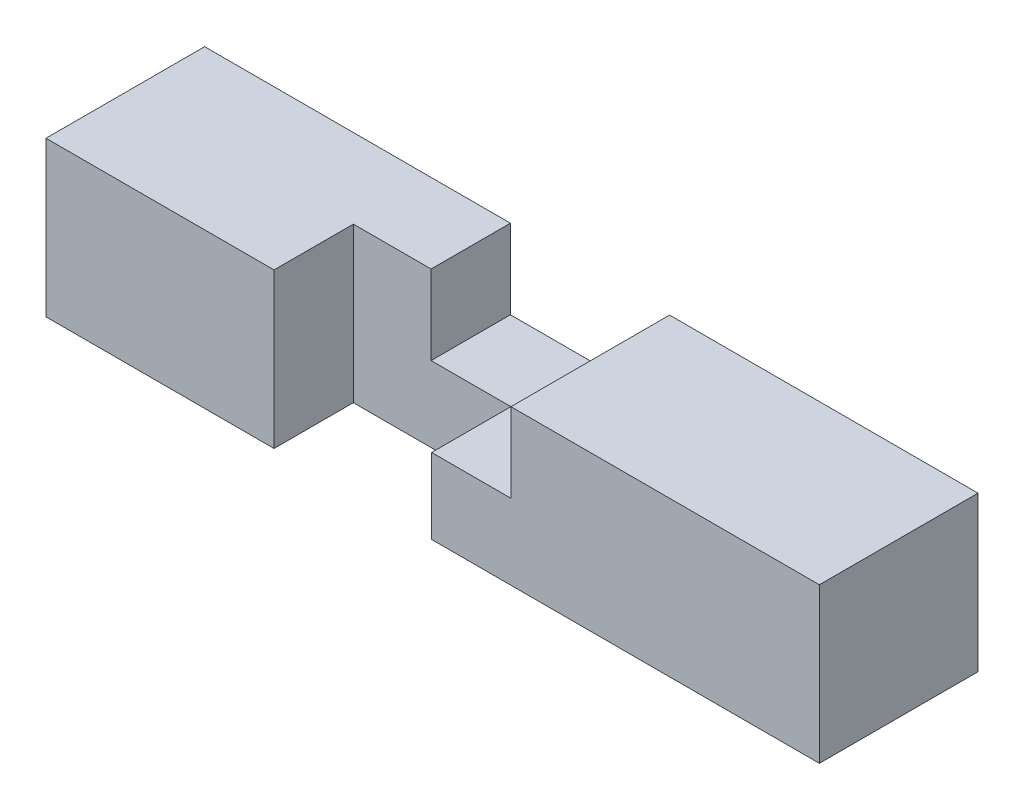
SolidWorks part; units mm, degrees
ref_plane "前基準面" through (0, 0, 0) normal (0, 0, 1) x (1, 0, 0)
ref_plane "上基準面" through (0, 0, 0) normal (0, 1, 0) x (1, 0, 0)
ref_plane "右基準面" through (0, 0, 0) normal (1, 0, 0) x (0, 0, -1)
sketch "草圖1" plane through (0, 0, 0) normal (0, 0, 1) x (1, 0, 0)
  line L1 (-48.75, 9.75) -> (48.75, 9.75)
  line L2 (-48.75, 9.75) -> (-48.75, -9.75)
  line L3 (-48.75, -9.75) -> (48.75, -9.75)
  line L4 (48.75, 9.75) -> (48.75, -9.75)
  line L5 (0, -9.75) -> (0, 9.75) construction
  line L6 (-48.75, 0) -> (48.75, 0) construction
  point P0 (0, 0)
extrude "填料-伸長1" add sketch "草圖1" along normal blind 20
sketch "草圖2" plane through (0, 9.75, 0) normal (0, 1, 0) x (1, 0, 0)
  line L0 (0, 0) -> (0, -20) construction
  line L3 (-50, -10) -> (50, -10) construction
  line L11 (0, -10) -> (0, -30) construction
  line L12 (20, -20) -> (-20, -20) construction
  line L13 (-20, -10) -> (-20, -20)
  line L15 (-20, -10) -> (9.8653, -10)
  line L17 (-20, -20) -> (9.8653, -20)
  line L18 (9.8653, -10) -> (9.8653, -20)
extrude "除料-伸長4" cut sketch "草圖2" against normal blind 29
sketch "草圖3" plane through (0, 9.75, 0) normal (0, 1, 0) x (1, 0, 0)
  line L0 (48.75, -20) -> (9.8653, -20) construction
  line L1 (9.8653, -10) -> (19.8653, -10)
  line L2 (9.8653, -10) -> (9.8653, -20)
  line L3 (9.8653, -20) -> (19.8653, -20)
  line L4 (19.8653, -10) -> (19.8653, -20)
extrude "除料-伸長5" cut sketch "草圖3" against normal blind 10
sketch "草圖4" plane through (0, 9.75, 0) normal (0, 1, 0) x (1, 0, 0)
  line L0 (0, 0) -> (-0.0674, -10) construction
  line L1 (48.75, 0) -> (-48.75, 0) construction
  line L2 (19.8653, -10) -> (-20, -10) construction
  line L4 (0, 0) -> (19.8653, 0)
  line L5 (0, 0) -> (0, -10)
  line L6 (0, -10) -> (19.8653, -10)
  line L7 (19.8653, 0) -> (19.8653, -10)
extrude "除料-伸長6" cut sketch "草圖4" against normal blind 10
sketch "草圖5" plane through (0, 9.75, 0) normal (0, 1, 0) x (1, 0, 0)
  line L0 (0, -10) -> (-20, -10) construction
  line L1 (0, 0) -> (-10, 0)
  line L2 (0, 0) -> (0, -10)
  line L3 (0, -10) -> (-10, -10)
  line L4 (-10, 0) -> (-10, -10)
extrude "除料-伸長7" cut sketch "草圖5" against normal blind 10
shell "薄殼1" thickness 2
sketch "草圖7" plane through (0, 9.75, 0) normal (0, 1, 0) x (1, 0, 0)
  line L1 (-20, -10) -> (-10, -10)
  line L2 (-20, -10) -> (-20, 0)
  line L3 (-20, 0) -> (-10, 0)
  line L4 (-10, -10) -> (-10, 0)
extrude "除料-伸長8" cut sketch "草圖7" against normal blind 10
sketch "草圖8" plane through (0, 9.75, 0) normal (0, 1, 0) x (1, 0, 0)
  line L0 (-20, 0) -> (-20, -20) construction
  line L1 (-20, -10) -> (-30.002, -10)
  line L2 (-20, -10) -> (-20, -20)
  line L3 (-20, -20) -> (-30.002, -20)
  line L4 (-30.002, -10) -> (-30.002, -20)
  line L5 (-20, -20) -> (-48.75, -20) construction
extrude "除料-伸長9" cut sketch "草圖8" against normal blind 10
sketch "草圖9" plane through (0, -0.25, 0) normal (0, 1, 0) x (1, 0, 0)
  line L1 (9.8653, -10) -> (-0.1347, -10)
  line L2 (9.8653, -10) -> (9.8653, -20)
  line L3 (9.8653, -20) -> (-0.1347, -20)
  line L4 (-0.1347, -10) -> (-0.1347, -20)
extrude "填料-伸長3" add sketch "草圖9" against normal blind 10
sketch "草圖10" plane through (0, -0.25, 0) normal (0, 1, 0) x (1, 0, 0)
  line L1 (-22, -18) -> (-30.5, -18)
  line L2 (-22, -18) -> (-22, -9.3085)
  line L3 (-22, -9.3085) -> (-30.5, -9.3085)
  line L4 (-30.5, -18) -> (-30.5, -9.3085)
extrude "填料-伸長4" add sketch "草圖10" against normal blind 0.5
sketch "草圖11" plane through (-30.002, 0, 0) normal (1, 0, 0) x (0, 0, -1)
  line L1 (-18, -0.25) -> (-10, -0.25)
  line L2 (-18, -0.25) -> (-18, 7.75)
  line L3 (-18, 7.75) -> (-10, 7.75)
  line L4 (-10, -0.25) -> (-10, 7.75)
extrude "填料-伸長5" add sketch "草圖11" against normal blind 0.5
sketch "草圖15" plane through (0, -0.25, 0) normal (0, 1, 0) x (1, 0, 0)
  line L1 (-30.5, -9.3085) -> (-20, -9.3085)
  line L2 (-30.5, -9.3085) -> (-30.5, -10)
  line L3 (-30.5, -10) -> (-20, -10)
  line L4 (-20, -9.3085) -> (-20, -10)
extrude "填料-伸長18" add sketch "草圖15" along normal blind 9.5
sketch "草圖18" plane through (0, -0.25, 0) normal (0, 1, 0) x (1, 0, 0)
  line L1 (-20, -10) -> (-12, -10)
  line L2 (-20, -10) -> (-20, -2)
  line L3 (-20, -2) -> (-12, -2)
  line L4 (-12, -10) -> (-12, -2)
extrude "填料-伸長22" add sketch "草圖18" against normal blind 0.5
sketch "草圖21" plane through (-20, 0, 0) normal (1, 0, 0) x (0, 0, -1)
  line L1 (-10, -0.25) -> (0, -0.25)
  line L2 (-10, -0.25) -> (-10, -0.3442)
  line L3 (-10, -0.3442) -> (0, -0.3442)
  line L4 (0, -0.25) -> (0, -0.3442)
extrude "填料-伸長25" add sketch "草圖21" along normal blind 10.5
sketch "草圖23" plane through (19.8653, 0, 0) normal (-1, 0, 0) x (0, 0, 1)
  line L1 (0, -0.25) -> (20, -0.25)
  line L2 (0, -0.25) -> (0, 9.75)
  line L3 (0, 9.75) -> (20, 9.75)
  line L4 (20, -0.25) -> (20, 9.75)
extrude "填料-伸長27" add sketch "草圖23" along normal blind 10
sketch "草圖24" plane through (0, -0.25, 0) normal (0, 1, 0) x (1, 0, 0)
  line L1 (-20, -10) -> (-30.002, -10)
  line L2 (-20, -10) -> (-20, -20)
  line L3 (-20, -20) -> (-30.002, -20)
  line L4 (-30.002, -10) -> (-30.002, -20)
extrude "填料-伸長28" add sketch "草圖24" along normal blind 10
sketch "草圖25" plane through (0, -0.25, 0) normal (0, 1, 0) x (1, 0, 0)
  line L0 (9.8653, 0) -> (-20, 0) construction
  line L1 (-20, -10) -> (-10.2, -10)
  line L2 (-20, -10) -> (-20, 0)
  line L3 (-20, 0) -> (-10.2, 0)
  line L4 (-10.2, -10) -> (-10.2, 0)
extrude "填料-伸長29" add sketch "草圖25" along normal blind 10
sketch "草圖31" plane through (9.8653, 0, 0) normal (1, 0, 0) x (0, 0, -1)
  line L1 (-20, -10.25) -> (-10, -10.25)
  line L2 (-20, -10.25) -> (-20, -9.75)
  line L3 (-20, -9.75) -> (-10, -9.75)
  line L4 (-10, -10.25) -> (-10, -9.75)
extrude "除料-伸長11" cut sketch "草圖31" against normal blind 11.5
sketch "草圖32" plane through (48.75, 0, 0) normal (1, 0, 0) x (0, 0, -1)
  line L1 (-18, -7.75) -> (-2, -7.75)
  line L2 (-18, -7.75) -> (-18, 7.75)
  line L3 (-18, 7.75) -> (-2, 7.75)
  line L4 (-2, -7.75) -> (-2, 7.75)
extrude "填料-伸長43" add sketch "草圖32" against normal blind 0.5
